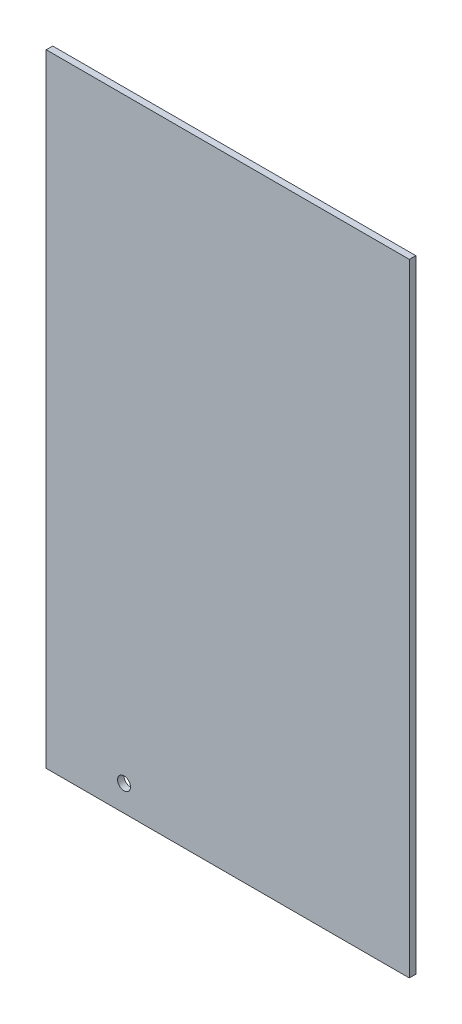
SolidWorks part; units mm, degrees
ref_plane "Front Plane" through (0, 0, 0) normal (0, 0, 1) x (1, 0, 0)
ref_plane "Top Plane" through (0, 0, 0) normal (0, 1, 0) x (1, 0, 0)
ref_plane "Right Plane" through (0, 0, 0) normal (1, 0, 0) x (0, 0, -1)
sketch "Sketch1" plane through (0, 0, 0) normal (0, 0, 1) x (1, 0, 0)
  line L0 (0, 0) -> (177.8, 0)
  line L1 (177.8, 0) -> (177.8, 304.8)
  line L2 (177.8, 304.8) -> (0, 304.8)
  line L3 (0, 304.8) -> (0, 0)
  circle A0 centre (38.1, 12.7) radius 3.175
  dimension "D3" = 6.35
  dimension "D1" = 177.8
  dimension "D2" = 304.8
  dimension "D4" = 12.7
  dimension "D5" = 38.1
extrude "Boss-Extrude1" add sketch "Sketch1" along normal blind 3.175
